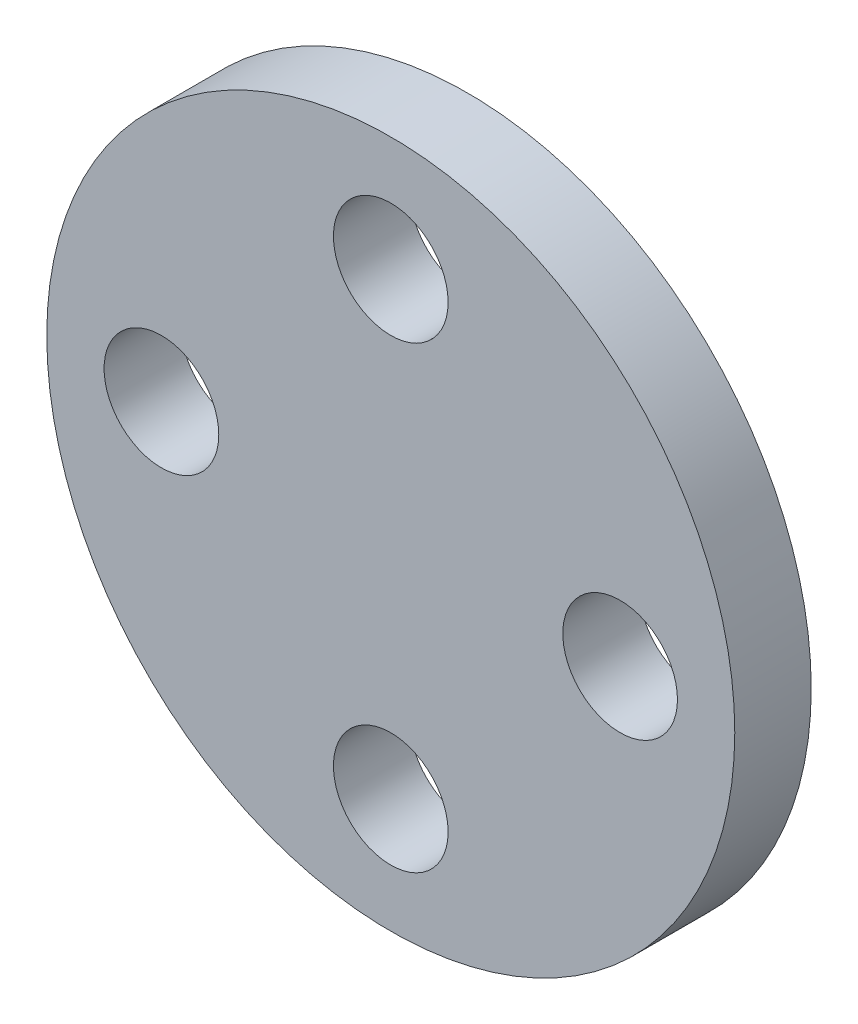
SolidWorks part; units mm, degrees
ref_plane "Front Plane" through (0, 0, 0) normal (0, 0, 1) x (1, 0, 0)
ref_plane "Top Plane" through (0, 0, 0) normal (0, 1, 0) x (1, 0, 0)
ref_plane "Right Plane" through (0, 0, 0) normal (1, 0, 0) x (0, 0, -1)
sketch "Sketch1" plane through (0, 0, 0) normal (0, 0, 1) x (1, 0, 0)
  circle A0 centre (0, 0) radius 14.2875
  circle A1 centre (0, 9.525) radius 2.3812
  circle A2 centre (9.525, 0) radius 2.3813
  circle A3 centre (0, -9.525) radius 2.3813
  circle A4 centre (-9.525, 0) radius 2.3813
  point P14 (0, 0)
  dimension "D1" = 28.575
  dimension "D2" = 4.7625
  dimension "D3" = 9.525
  dimension "D4" = 4
extrude "Boss-Extrude1" add sketch "Sketch1" along normal blind 3.175
